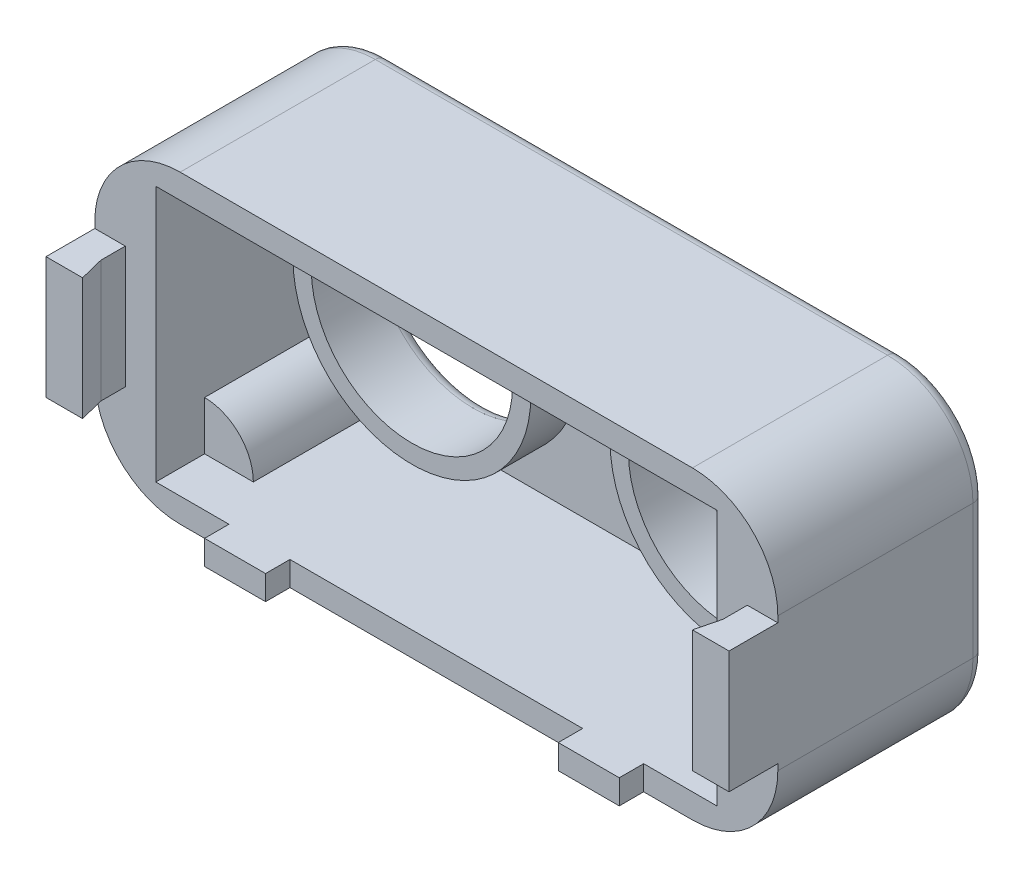
SolidWorks part; units mm, degrees
ref_plane "Front Plane" through (0, 0, 0) normal (0, 0, 1) x (1, 0, 0)
ref_plane "Top Plane" through (0, 0, 0) normal (0, 1, 0) x (1, 0, 0)
ref_plane "Right Plane" through (0, 0, 0) normal (1, 0, 0) x (0, 0, -1)
sketch "Sketch1" plane through (0, 0, 0) normal (0, 0, 1) x (1, 0, 0)
  line L0 (0, 0) -> (0, 26.5794) construction
  line L1 (0, 0) -> (-41.1508, 0) construction
  circle A0 centre (-13, 0) radius 8.25
  circle A1 centre (13, 0) radius 8.25
  dimension "D1" = 16.5
  dimension "D2" = 26
sketch "Sketch2" plane through (0, 0, 0) normal (0, 0, 1) x (1, 0, 0)
  line L0 (0, -1.7585) -> (0, 19.056) construction
  line L1 (3.2805, 0) -> (-32.4053, 0) construction
  line L2 (-28, 12.5) -> (28, 12.5)
  line L3 (-23, -10.5) -> (23, -10.5)
  line L4 (-23, -10.5) -> (-23, 10.5)
  line L5 (-23, 10.5) -> (23, 10.5)
  line L6 (23, -10.5) -> (23, 10.5)
  line L7 (-23, -10.5) -> (23, 10.5) construction
  line L8 (-23, 10.5) -> (23, -10.5) construction
  line L9 (28, -12.5) -> (28, 12.5)
  line L10 (-28, -12.5) -> (28, -12.5)
  line L11 (-28, -12.5) -> (-28, 12.5)
  point P5 (0, 0)
  dimension "D1" = 21
  dimension "D2" = 46
  dimension "D4" = 5
  dimension "D3" = 2
  dimension "D5" = 2
  dimension "D6" = 5
extrude "Box" add sketch "Sketch2" along normal blind 15
sketch "Sketch3" plane through (0, 0, 0) normal (0, 0, -1) x (-1, 0, 0)
  line L0 (28, -12.5) -> (-28, -12.5) construction
  line L1 (-28, 12.5) -> (28, 12.5)
  line L2 (-28, 12.5) -> (-28, -12.5)
  line L3 (-28, -12.5) -> (28, -12.5)
  line L4 (28, 12.5) -> (28, -12.5)
extrude "Front" add sketch "Sketch3" along normal blind 2
sketch "Sketch8" plane through (0, 0, 0) normal (0, 0, 1) x (1, 0, 0)
  line L0 (0, 7.8229) -> (0, -15.4038) construction
  circle A1 centre (-13, 0) radius 9.75
  circle A2 centre (13, 0) radius 9.75
extrude "Boss-Extrude7" add sketch "Sketch8" along normal blind 4
extrude "Cut-Extrude1" cut sketch "Sketch1" against normal through all and the other way up to next
fillet "Fillet1" radius 7 4 edges at (28, -12.5, 6.5) (28, 12.5, 6.5) (-28, -12.5, 6.5) (-28, 12.5, 6.5)
sketch "Sketch4" plane through (0, 0, 0) normal (0, 0, 1) x (1, 0, 0)
  line L0 (-23, 6.5) -> (-23, 10.5)
  line L1 (-23, 10.5) -> (-19, 10.5)
  line L2 (19, 10.5) -> (23, 10.5)
  line L3 (23, 10.5) -> (23, 6.5)
  line L4 (-23, -6.5) -> (-23, -10.5)
  line L5 (-23, -10.5) -> (-19, -10.5)
  line L6 (23, -6.5) -> (23, -10.5)
  line L7 (23, -10.5) -> (19, -10.5)
  arc A0 (-23, 6.5) -> (-19, 10.5) centre (-23, 10.5) ccw
  arc A1 (19, 10.5) -> (23, 6.5) centre (23, 10.5) ccw
  arc A2 (23, -6.5) -> (19, -10.5) centre (23, -10.5) ccw
  arc A3 (-19, -10.5) -> (-23, -6.5) centre (-23, -10.5) ccw
  dimension "D1" = 8
extrude "Boss-Extrude3" add sketch "Sketch4" along normal blind 11
sketch "Sketch5" plane through (0, 0, 15) normal (0, 0, 1) x (1, 0, 0)
  line L0 (32.8077, 0) -> (-34.7934, 0) construction
  line L1 (0, -18.1737) -> (0, 16.6197) construction
  line L2 (-28, 5.5) -> (-28, -5.5) construction
  line L3 (-28, 5) -> (-25.5, 5)
  line L4 (-28, 5) -> (-28, -5)
  line L5 (-28, -5) -> (-25.5, -5)
  line L6 (-25.5, 5) -> (-25.5, -5)
  line L11 (25.5, 5) -> (25.5, -5)
  line L12 (28, -5) -> (25.5, -5)
  line L13 (28, 5) -> (28, -5)
  line L14 (28, 5) -> (25.5, 5)
  dimension "D1" = 10
  dimension "D2" = 2.5
fillet "Fillet2" radius 1 8 edges at (-25.9497, 10.4497, -2) (-28, 0, -2) (-25.9497, -10.4497, -2) (0, -12.5, -2) (25.9497, -10.4497, -2) (28, 0, -2) (25.9497, 10.4497, -2) (0, 12.5, -2)
fillet "Fillet3" radius 1 2 edges at (-4.75, 0, -2) (4.75, 0, -2)
extrude "Boss-Extrude4" add sketch "Sketch5" along normal blind 4
sketch "Sketch6" plane through (0, 0, 15) normal (0, 0, 1) x (1, 0, 0)
  line L0 (0, 19.0899) -> (0, -20.4248) construction
  line L1 (-21, -12.5) -> (21, -12.5) construction
  line L2 (-17, -12.5) -> (-12, -12.5)
  line L3 (-17, -12.5) -> (-17, -10.5)
  line L4 (-17, -10.5) -> (-12, -10.5)
  line L5 (-12, -12.5) -> (-12, -10.5)
  line L6 (-23, -10.5) -> (23, -10.5) construction
  line L7 (12, -12.5) -> (12, -10.5)
  line L8 (17, -10.5) -> (12, -10.5)
  line L9 (17, -12.5) -> (17, -10.5)
  line L10 (17, -12.5) -> (12, -12.5)
  dimension "D1" = 12
  dimension "D2" = 5
extrude "Boss-Extrude5" add sketch "Sketch6" along normal blind 2
sketch "Sketch7" plane through (0, 5, 0) normal (0, 1, 0) x (1, 0, 0)
  line L0 (-25.5, -17) -> (-25, -19)
  line L1 (-25.5, -19) -> (-25.5, -15) construction
  line L2 (-25, -19) -> (-25.5, -19)
  line L3 (-25.5, -19) -> (-25.5, -17)
  line L4 (0, 4.7102) -> (0, -22.4279) construction
  line L5 (25.5, -19) -> (25.5, -17)
  line L6 (25, -19) -> (25.5, -19)
  line L7 (25.5, -17) -> (25, -19)
  dimension "D1" = 0.5
extrude "Boss-Extrude6" add sketch "Sketch7" against normal blind 10
